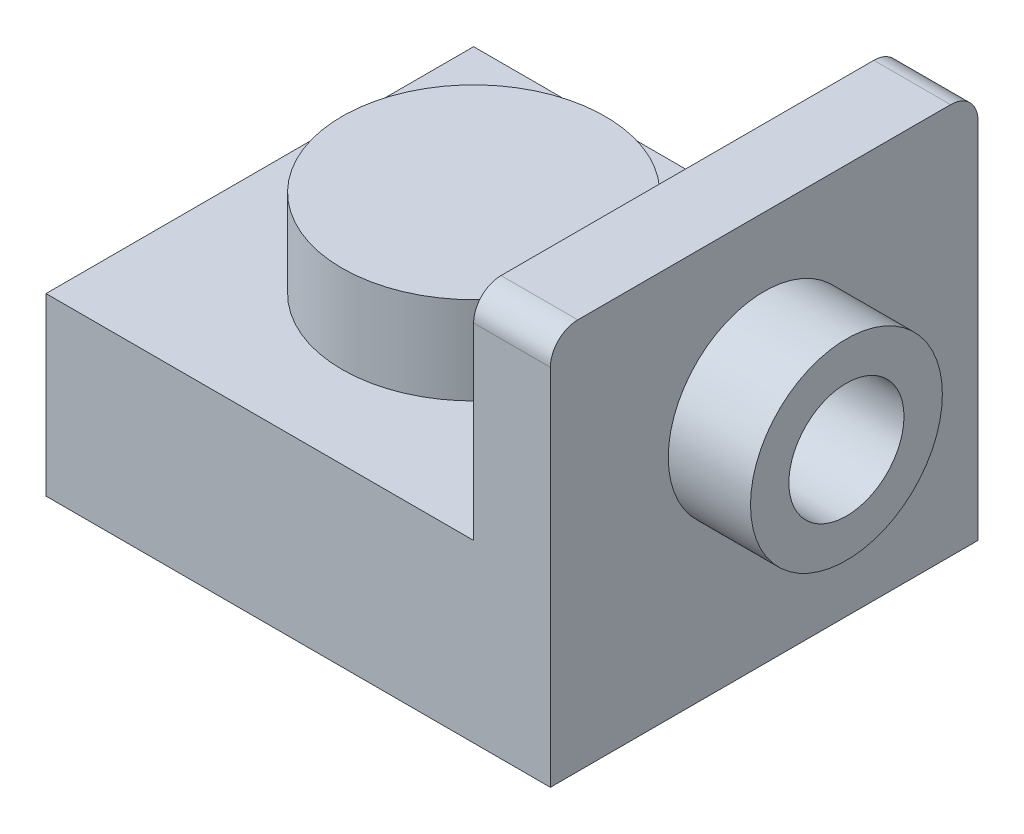
SolidWorks part; units mm, degrees
material "ABS"
ref_plane "Front Plane" through (0, 0, 0) normal (0, 0, 1) x (1, 0, 0)
ref_plane "Top Plane" through (0, 0, 0) normal (0, 1, 0) x (1, 0, 0)
ref_plane "Right Plane" through (0, 0, 0) normal (1, 0, 0) x (0, 0, -1)
sketch "Sketch1" plane through (0, 0, 0) normal (0, 0, 1) x (1, 0, 0)
  line L1 (0, 0) -> (7.8, 0)
  line L2 (0, 0) -> (0, 3.2)
  line L3 (0, 3.2) -> (7.8, 3.2)
  line L4 (7.8, 0) -> (7.8, 3.2)
  line L5 (0, 0) -> (7.8, 3.2) construction
  line L6 (0, 3.2) -> (7.8, 0) construction
  point P4 (3.9, 1.6)
  dimension "D1" = 7.8
  dimension "D2" = 3.2
extrude "Boss-Extrude1" add sketch "Sketch1" against normal blind 7.8
sketch "Sketch2" plane through (0, 3.2, 0) normal (0, 1, 0) x (1, 0, 0)
  line L0 (7.8, 0) -> (0, 0) construction
  circle A0 centre (3.9, 3.9) radius 2.4
  dimension "D1" = 4.8
  dimension "D2" = 3.9
  dimension "D3" = 3.9
extrude "Boss-Extrude2" add sketch "Sketch2" along normal blind 1.6
sketch "Sketch3" plane through (0, 0, 0) normal (0, -1, 0) x (1, 0, 0)
  line L0 (7.7, -6.6) -> (1.2, -6.6)
  line L1 (1.2, -6.6) -> (1.2, -1.2)
  line L2 (1.2, -1.2) -> (7.7, -1.2)
  line L3 (7.7, -1.2) -> (7.7, -6.6)
  line L4 (0, 0) -> (7.8, 0) construction
  line L5 (0, -7.8) -> (0, 0) construction
  line L6 (7.8, -7.8) -> (7.8, 0) construction
  line L7 (0, -7.8) -> (7.8, -7.8) construction
  point P6 (3.9, 0)
  point P11 (7.8, -3.9)
  dimension "D1" = 1.2
  dimension "D2" = 1.2
  dimension "D3" = 0.1
  dimension "D4" = 1.2
extrude "Cut-Extrude1" cut sketch "Sketch3" against normal offset from surface (3 mm away) 0.2 up to face at (3.9, 3.2, -1.5)
sketch "Sketch4" plane through (0, 3, 0) normal (0, -1, 0) x (1, 0, 0)
  line L1 (0, -7.8) -> (0, 0) construction
  line L2 (0, 0) -> (7.8, 0) construction
  circle A0 centre (3.9, -3.9) radius 1.3
  dimension "D2" = 2.6
  dimension "D1" = 3.9
  dimension "D3" = 3.9
extrude "Cut-Extrude2" cut sketch "Sketch4" against normal blind 1.7
ref_plane "Plane1" through (7.8, 0, 0) normal (1, 0, 0) x (0, 0, -1)
sketch "Sketch5" plane through (7.8, 0, 0) normal (1, 0, 0) x (0, 0, -1)
  line L0 (0, 0) -> (0, 7.1346)
  line L1 (0, 7.1346) -> (7.8, 7.1346)
  line L2 (7.8, 7.1346) -> (7.8, 0)
  line L3 (7.8, 0) -> (0, 0)
extrude "Boss-Extrude3" add sketch "Sketch5" along normal blind 1.4
fillet "Fillet1" radius 0.5 2 edges at (8.5, 7.1346, -7.8) (8.5, 7.1346, 0)
sketch "Sketch6" plane through (9.2, 0, 0) normal (1, 0, 0) x (0, 0, -1)
  line L0 (7.3, 7.1346) -> (0.5, 7.1346) construction
  line L1 (7.8, 0) -> (7.8, 6.6346) construction
  circle A0 centre (3.9, 4.1346) radius 1.75
  circle A1 centre (3.9, 4.1346) radius 1.05
  dimension "D3" = 3.5
  dimension "D4" = 0.7
  dimension "D1" = 3
  dimension "D2" = 3.9
extrude "Boss-Extrude4" add sketch "Sketch6" along normal blind 1.5
